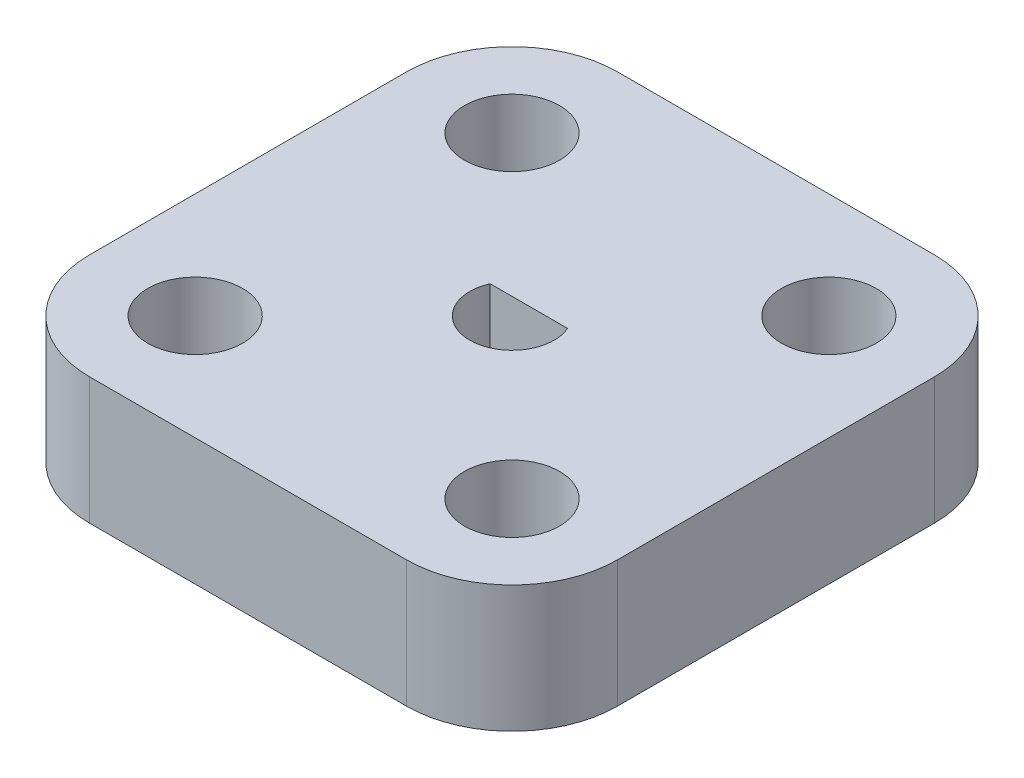
SolidWorks part; units mm, degrees
ref_plane "Front Plane" through (0, 0, 0) normal (0, 0, 1) x (1, 0, 0)
ref_plane "Top Plane" through (0, 0, 0) normal (0, 1, 0) x (1, 0, 0)
ref_plane "Right Plane" through (0, 0, 0) normal (1, 0, 0) x (0, 0, -1)
sketch "Sketch1" plane through (0, 0, 0) normal (0, 1, 0) x (1, 0, 0)
  line L0 (-1.833, 0.8) -> (1.833, 0.8)
  line L1 (-7.5, 12.5) -> (7.5, 12.5)
  line L2 (-12.5, 7.5) -> (-12.5, -7.5)
  line L3 (-7.5, -12.5) -> (7.5, -12.5)
  line L4 (12.5, 7.5) -> (12.5, -7.5)
  line L5 (-12.5, 12.5) -> (12.5, -12.5) construction
  line L6 (-12.5, -12.5) -> (12.5, 12.5) construction
  arc A0 (-12.5, -7.5) -> (-7.5, -12.5) centre (-7.5, -7.5) ccw
  arc A1 (7.5, -12.5) -> (12.5, -7.5) centre (7.5, -7.5) ccw
  arc A2 (7.5, 12.5) -> (12.5, 7.5) centre (7.5, 7.5) cw
  arc A3 (-7.5, 12.5) -> (-12.5, 7.5) centre (-7.5, 7.5) ccw
  circle A4 centre (0, 0) radius 2
  point P0 (0, 0)
  dimension "D3" = 5
  dimension "D4" = 4
  dimension "D1" = 25
  dimension "D2" = 25
  dimension "D5" = 0.8
extrude "Boss-Extrude1" add sketch "Sketch1" along normal blind 6 contours L0 A4 | L1 A3 L2 A0 L3 A1 L4 A2 A4
hole_wizard "#8 Clearance Hole1" positions "Sketch2" profile "Sketch3" hole size "#8" standard "ANSI Inch" end condition through all
sketch "Sketch2" plane through (0, 6, 0) normal (0, 1, 0) x (1, 0, 0)
  point P0 (-7.5, 7.5)
  point P2 (7.5, 7.5)
  point P4 (-7.5, -7.5)
  point P6 (7.5, -7.5)
  dimension "D1" = 15
  dimension "D2" = 15
  dimension "D3" = 7.5
  dimension "D4" = 7.5
sketch "Sketch3" plane through (-7.5, 6, -7.5) normal (1, 0, 0) x (0, 0, 1)
  line L0 (0, 0) -> (0, 6)
  line L1 (0, 6) -> (2.2479, 6)
  line L2 (2.2479, 6) -> (2.2479, 0)
  line L5 (2.2479, 0) -> (0, 0)
  line L11 (0, -6.35) -> (0, 107.95) construction
  dimension "Thru Hole Dia." = 4.4958
  dimension "Thru Hole Depth" = 6
equation "\"D2@Sketch1\"=\"D1@Sketch1\""
equation "\"D3@Sketch2\"=\"D1@Sketch2\"/2"
equation "\"D4@Sketch2\"=\"D2@Sketch2\"/2"
equation "\"D5@Sketch1\"=2.8-\"D4@Sketch1\"/2"
